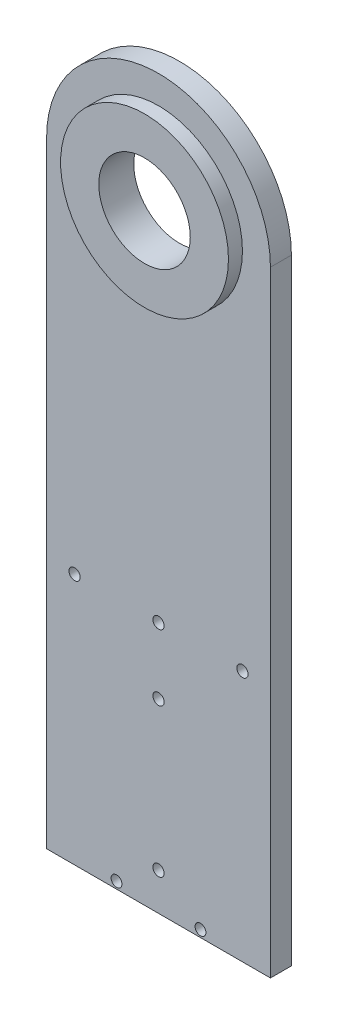
SolidWorks part; units mm, degrees
material "ABS"
ref_plane "Front Plane" through (0, 0, 0) normal (0, 0, 1) x (1, 0, 0)
ref_plane "Top Plane" through (0, 0, 0) normal (0, 1, 0) x (1, 0, 0)
ref_plane "Right Plane" through (0, 0, 0) normal (1, 0, 0) x (0, 0, -1)
sketch "Sketch1" plane through (0, 0, 0) normal (0, 0, 1) x (1, 0, 0)
  line L0 (0, 371.5879) -> (0, -87.2741) construction
  line L1 (-50.8, 0) -> (50.8, 0)
  line L2 (50.8, 0) -> (50.8, 279.4)
  line L4 (-50.8, 279.4) -> (-50.8, 0)
  arc A0 (50.8, 279.4) -> (-50.8, 279.4) centre (0, 279.4) ccw
  dimension "D3" = 101.6
  dimension "D1" = 50.8
  dimension "D2" = 50.8
  dimension "D4" = 279.4
extrude "Boss-Extrude1" add sketch "Sketch1" along normal blind 9.525
sketch "Sketch2" plane through (0, 0, 9.525) normal (0, 0, 1) x (1, 0, 0)
  circle A0 centre (0, 279.4) radius 38.1
  dimension "D1" = 76.2
extrude "Boss-Extrude2" add sketch "Sketch2" along normal blind 6.35
sketch "Sketch3" plane through (0, 0, 15.875) normal (0, 0, 1) x (1, 0, 0)
  circle A0 centre (0, 279.4) radius 20.7645
  dimension "D1" = 41.529
extrude "Cut-Extrude1" cut sketch "Sketch3" against normal through all
hole_wizard "#10 (0.1935) Diameter Hole1" positions "Sketch7" profile "Sketch8" hole size "#10" standard "Ansi Inch"
sketch "Sketch7" plane through (0, 0, 0) normal (0, 0, -1) x (-1, 0, 0)
  line L0 (-50.8, 0) -> (-50.8, 279.4) construction
  line L1 (50.8, 0) -> (-50.8, 0) construction
  point P0 (-19.05, 3.175)
  point P1 (19.05, 3.175)
  dimension "D1" = 31.75
  dimension "D2" = 38.1
  dimension "D3" = 3.175
sketch "Sketch8" plane through (19.05, 3.175, 0) normal (1, 0, 0) x (0, 1, 0)
  line L0 (0, 0) -> (0, 11.6366)
  line L1 (0, 11.6366) -> (2.4574, 10.16)
  line L2 (2.4574, 10.16) -> (2.4574, 0)
  line L5 (2.4574, 0) -> (0, 0)
  line L10 (0, 11.6366) -> (-2.4574, 10.16) construction
  line L11 (0, -6.35) -> (0, 107.95) construction
  dimension "Hole Dia." = 4.9149
  dimension "Hole Depth" = 10.16
  dimension "Drill Angle" = 118
hole_wizard "#10 Clearance Hole1" positions "Sketch10" profile "Sketch9" hole size "#10" standard "Ansi Inch" end condition through all
sketch "Sketch10" plane through (0, 0, 0) normal (0, 0, -1) x (-1, 0, 0)
  line L0 (0, 0) -> (0, 258.6355) construction
  line L2 (-50.8, 0) -> (-50.8, 279.4) construction
  line L3 (50.8, 279.4) -> (50.8, 0) construction
  line L4 (-50.8, 16.9901) -> (50.8, 16.9901) construction
  line L6 (-38.1, 0) -> (-38.1, 159.8763) construction
  line L7 (50.8, 0) -> (-50.8, 0) construction
  line L8 (38.1, 0) -> (38.1, 156.407) construction
  line L9 (-50.8, 114.3) -> (50.8, 114.3) construction
  circle A0 centre (0, 279.4) radius 20.7645 construction
  point P0 (0, 84.3001)
  point P1 (0, 16.9901)
  point P24 (-38.1, 114.3)
  point P26 (0, 114.3)
  point P28 (38.1, 114.3)
  dimension "D1" = 12.7
  dimension "D2" = 29.9999
  dimension "D3" = 12.7
  dimension "D4" = 67.31
sketch "Sketch9" plane through (0, 84.3001, 0) normal (1, 0, 0) x (0, 1, 0)
  line L0 (0, 0) -> (0, 15.875)
  line L1 (0, 15.875) -> (2.5527, 15.875)
  line L2 (2.5527, 15.875) -> (2.5527, 0)
  line L5 (2.5527, 0) -> (0, 0)
  line L11 (0, -6.35) -> (0, 107.95) construction
  dimension "Thru Hole Dia." = 5.1054
  dimension "Thru Hole Depth" = 15.875
